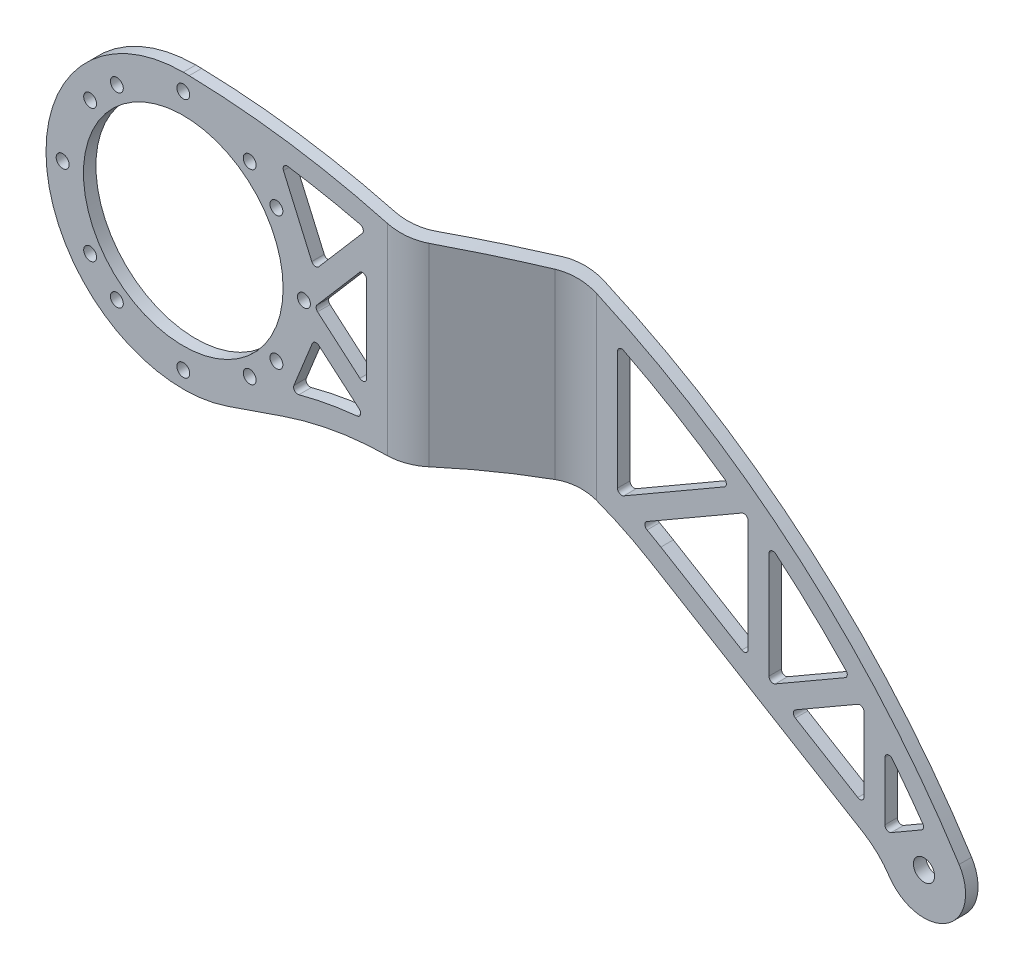
SolidWorks part; units mm, degrees
material "6061 合金"
ref_plane "前视基准面" through (0, 0, 0) normal (0, 0, 1) x (1, 0, 0)
ref_plane "上视基准面" through (0, 0, 0) normal (0, 1, 0) x (1, 0, 0)
ref_plane "右视基准面" through (0, 0, 0) normal (1, 0, 0) x (0, 0, -1)
other "Configuration Table"
sketch "草图1" plane through (0, 0, 0) normal (0, 0, 1) x (1, 0, 0)
  line L0 (-38.6665, 0) -> (31.2744, 0) construction
  line L1 (0, 22.4607) -> (0, -30.1372) construction
  line L4 (10.7304, -31.2067) -> (23.987, -26.6485)
  line L5 (91.2325, -33.7454) -> (142.3676, -64.5004)
  line L6 (157.0595, -65.0562) -> (0, 0) construction
  circle A7 centre (157.0595, -65.0562) radius 2.55
  arc A9 (0, 33) -> (10.7304, -31.2067) centre (0, 0) ccw
  arc A10 (148.7262, -70.5839) -> (165.4995, -59.6928) centre (157.0595, -65.0562) ccw
  arc A11 (1.4146, 32.9833) -> (165.4995, -59.6928) centre (-3.3007, -166.9611) cw
  arc A12 (23.987, -26.6485) -> (91.2325, -33.7454) centre (50, -102.3011) cw
  arc A13 (142.3676, -64.5004) -> (148.7262, -70.5839) centre (132.0595, -81.6393) cw
  arc A14 (1.4146, 32.9833) -> (0, 33) centre (0, -27) ccw
  dimension "D1" = 60
  dimension "D2" = 5.1
  dimension "D3" = 22.5
  dimension "D4" = 33
  dimension "D6" = 80
  dimension "D7" = 20
  dimension "D8" = 10
  dimension "D10" = 200
  dimension "D11" = 50
  dimension "D5" = 130
  dimension "D9" = 170
  dimension "D12" = 25
extrude "凸台-拉伸1" add sketch "草图1" along normal blind 3 and the other way blind 21
sketch "草图6" plane through (0, 0, 0) normal (0, 1, 0) x (1, 0, 0)
  line L0 (-33, 0) -> (47.8579, 0)
  line L2 (54.9289, 2.9289) -> (73, 21)
  line L3 (10.7304, 21) -> (-33, 21) construction
  line L5 (53.2426, -3) -> (71.3137, 15.0711)
  line L7 (78.3848, 18) -> (167.0595, 18)
  line L8 (167.0595, 18) -> (167.0595, -3)
  line L9 (167.0595, -3) -> (53.2426, -3)
  line L10 (73, 21) -> (-33, 21)
  line L12 (-33, 21) -> (-33, 0)
  line L13 (-33, 21) -> (-33, -3) construction
  line L14 (167.0595, -3) -> (167.0595, 21) construction
  line L15 (165.4995, 21) -> (1.4146, 21) construction
  line L16 (1.4146, -3) -> (165.4995, -3) construction
  arc A0 (71.3137, 15.0711) -> (78.3848, 18) centre (78.3848, 8) cw
  arc A1 (47.8579, 0) -> (54.9289, 2.9289) centre (47.8579, 10) ccw
  point P25 (52, 0)
  dimension "D5" = 10
  dimension "D1" = 3
  dimension "D2" = 3
  dimension "D3" = 45
  dimension "D4" = 85
extrude "切除-拉伸3" cut sketch "草图6" against normal through all both and the other way through all
sketch "草图2" plane through (0, 0, 3) normal (0, 0, 1) x (1, 0, 0)
  circle A0 centre (-29, 0) radius 1.55
  circle A2 centre (0, 0) radius 29 construction
  circle A3 centre (0, -29) radius 1.55
  circle A4 centre (0, 29) radius 1.55
  circle A5 centre (29, 0) radius 1.55
  dimension "D2" = 3.1
  dimension "D1" = 29
extrude "切除-拉伸1" cut sketch "草图2" against normal through all
sketch "草图4" plane through (0, 0, 3) normal (0, 0, 1) x (1, 0, 0)
  line L0 (35.2189, 0) -> (0, 0) construction
  line L1 (0, 0) -> (0, 39.685) construction
  line L2 (22.3882, 15.9693) -> (0, 0) construction
  line L3 (0, 0) -> (15.9693, 22.3882) construction
  line L4 (15.9693, -22.3882) -> (0, 0) construction
  line L5 (0, 0) -> (22.3882, -15.9693) construction
  line L6 (-22.3882, -15.9693) -> (0, 0) construction
  line L7 (0, 0) -> (-15.9693, -22.3882) construction
  line L8 (-15.9693, 22.3882) -> (0, 0) construction
  line L9 (0, 0) -> (-22.3882, 15.9693) construction
  circle A0 centre (0, 0) radius 27.5 construction
  circle A1 centre (-22.3882, 15.9693) radius 1.55
  circle A2 centre (15.9693, 22.3882) radius 1.55
  circle A3 centre (-15.9693, -22.3882) radius 1.55
  circle A4 centre (22.3882, -15.9693) radius 1.55
  circle A5 centre (-15.9693, 22.3882) radius 1.55
  circle A6 centre (22.3882, 15.9693) radius 1.55
  circle A7 centre (15.9693, -22.3882) radius 1.55
  circle A8 centre (-22.3882, -15.9693) radius 1.55
  point P16 (0, 0)
  dimension "D1" = 55
  dimension "D5" = 3.1
  dimension "D2" = 35.5
  dimension "D3" = 19
  dimension "D4" = 4
extrude "切除-拉伸2" cut sketch "草图4" against normal through all
fillet "圆角2" radius 10 2 edges at (73, -3.8831, -21) (53.2426, 1.2564, 3)
sketch "草图10" plane through (0, 0, 3) normal (0, 0, 1) x (1, 0, 0)
  circle A0 centre (0, 0) radius 24
  dimension "D1" = 48
extrude "切除-拉伸5" cut sketch "草图10" against normal through all
sketch "草图12" plane through (0, 0, -18) normal (0, 0, 1) x (1, 0, 0)
  line L0 (83.3848, 6.0917) -> (83.3848, -22.3996)
  line L1 (84.8848, -23.2657) -> (109.0475, -9.3153)
  line L4 (93.8095, -29.4607) -> (144.9447, -60.2157)
  line L5 (83.3848, 7.7118) -> (83.3848, -24.1317)
  line L11 (113.2813, -12.6445) -> (90.4641, -25.818)
  line L12 (93.8095, -29.4607) -> (113.2659, -41.1626)
  line L13 (114.7813, -13.5105) -> (114.7813, -40.3057)
  line L14 (119.7813, -17.8314) -> (119.7813, -43.3492)
  line L15 (121.2813, -44.2152) -> (138.1188, -34.4941)
  line L16 (126.1486, -47.1786) -> (141.1555, -38.5143)
  line L17 (142.6555, -39.3804) -> (142.6555, -57.0705)
  line L18 (147.6555, -46.3571) -> (147.6555, -60.3684)
  line L19 (126.1332, -48.9016) -> (141.1401, -57.9274)
  line L20 (156.4448, -57.026) -> (149.1555, -61.2345)
  arc A0 (109.124, -7.6322) -> (84.8368, 6.9837) centre (-3.3007, -166.9611) ccw
  arc A1 (138.3452, -32.9408) -> (121.4209, -17.0627) centre (-3.3007, -166.9611) ccw
  arc A2 (161.2795, -62.3745) -> (83.3848, 7.7118) centre (-3.3007, -166.9611) ccw
  arc A4 (156.7656, -55.5888) -> (149.4388, -45.7354) centre (-3.3007, -166.9611) ccw
  arc A5 (149.4263, -63.6561) -> (144.9447, -60.2157) centre (132.0595, -81.6393) ccw construction
  arc A22 (152.8929, -67.82) -> (144.9447, -60.2157) centre (132.0595, -81.6393) ccw
  arc A24 (152.8929, -67.82) -> (161.2795, -62.3745) centre (157.0595, -65.0562) ccw
  arc A25 (147.6555, -46.3571) -> (149.4388, -45.7354) centre (148.6555, -46.3571) cw
  arc A26 (126.1486, -47.1786) -> (126.1332, -48.9016) centre (126.6486, -48.0446) ccw
  arc A27 (141.1555, -38.5143) -> (142.6555, -39.3804) centre (141.6555, -39.3804) cw
  arc A28 (138.1188, -34.4941) -> (138.3452, -32.9408) centre (137.6188, -33.628) ccw
  arc A29 (119.7813, -43.3492) -> (121.2813, -44.2152) centre (120.7813, -43.3492) ccw
  arc A30 (119.7813, -17.8314) -> (121.4209, -17.0627) centre (120.7813, -17.8314) cw
  arc A31 (114.7813, -40.3057) -> (113.2659, -41.1626) centre (113.7813, -40.3057) cw
  arc A32 (90.4641, -25.818) -> (90.4877, -27.5633) centre (90.9641, -26.684) ccw
  arc A33 (113.2813, -12.6445) -> (114.7813, -13.5105) centre (113.7813, -13.5105) cw
  arc A34 (109.0475, -9.3153) -> (109.124, -7.6322) centre (108.5475, -8.4493) ccw
  arc A35 (84.8848, -23.2657) -> (83.3848, -22.3996) centre (84.3848, -22.3996) cw
  arc A36 (84.8368, 6.9837) -> (83.3848, 6.0917) centre (84.3848, 6.0917) ccw
  arc A37 (142.6555, -57.0705) -> (141.1401, -57.9274) centre (141.6555, -57.0705) cw
  arc A38 (147.6555, -60.3684) -> (149.1555, -61.2345) centre (148.6555, -60.3684) ccw
  arc A39 (156.7656, -55.5888) -> (156.4448, -57.026) centre (155.9448, -56.16) cw
  arc A41 (93.8095, -29.4607) -> (83.3848, -24.1317) centre (50, -102.3011) ccw
  arc A42 (93.8095, -29.4607) -> (90.4877, -27.5633) centre (50, -102.3011) ccw
  point P19 (83.3848, -24.1317)
  point P21 (147.6555, -62.1005)
  point P30 (147.6555, -62.1005)
  point P35 (124.6791, -48.027)
  point P38 (142.6555, -37.6483)
  point P41 (139.212, -33.8629)
  point P44 (399.0304, 162.0422)
  point P45 (119.7813, -45.0813)
  point P54 (114.7813, -11.7784)
  point P57 (110.3955, -8.537)
  dimension "D6" = 60
  dimension "D9" = 5
  dimension "D2" = 5
  dimension "D11" = 60
  dimension "D12" = 1
  dimension "D13" = 1
  dimension "D7" = 1
  dimension "D3" = 5
  dimension "D4" = 60
  dimension "D5" = 60
  dimension "D8" = 5
  dimension "D1" = 5
extrude "切除-拉伸6" cut sketch "草图12" against normal through all
sketch "草图13" plane through (0, 0, 3) normal (0, 0, 1) x (1, 0, 0)
  line L0 (32.9388, 0) -> (0, 0) construction
  line L2 (24.0827, 24.5625) -> (30.8907, 9.0204)
  line L3 (32.565, 8.7697) -> (43.0399, 20.9561)
  line L4 (44.1005, -17.5061) -> (44.1005, 22.19)
  line L5 (9.1045, -26.4784) -> (22.3612, -21.9202)
  line L6 (44.1005, -8.7346) -> (44.1005, 11.822)
  line L8 (32.1804, 0.6518) -> (42.3422, 12.4738)
  line L9 (32.2869, -0.7584) -> (42.4487, -9.493)
  line L10 (32.5853, -7.6081) -> (42.2904, -15.9502)
  line L11 (31.0063, -7.9916) -> (26.5896, -18.9173)
  circle A0 centre (22.3882, -15.9693) radius 1.55 construction
  arc A1 (41.7358, -17.7038) -> (42.2904, -15.9502) centre (41.6386, -16.7085) ccw
  arc A2 (26.5896, -18.9173) -> (27.7781, -20.2573) centre (27.5167, -19.2921) ccw
  arc A3 (32.1804, 0.6518) -> (32.2869, -0.7584) centre (32.9388, 0) ccw
  arc A4 (32.5853, -7.6081) -> (31.0063, -7.9916) centre (31.9335, -8.3664) ccw
  arc A5 (42.4487, -9.493) -> (44.1005, -8.7346) centre (43.1005, -8.7346) ccw
  arc A6 (42.3422, 12.4738) -> (44.1005, 11.822) centre (43.1005, 11.822) cw
  arc A7 (30.8907, 9.0204) -> (32.565, 8.7697) centre (31.8066, 9.4216) ccw
  arc A8 (43.0399, 20.9561) -> (42.5165, 22.5799) centre (42.2815, 21.6079) ccw
  arc A9 (24.0827, 24.5625) -> (25.1446, 25.9531) centre (24.9987, 24.9638) cw
  circle A10 centre (22.3882, 15.9693) radius 1.55 construction
  arc A18 (44.1005, -17.5061) -> (22.3612, -21.9202) centre (50, -102.3011) ccw
  arc A19 (44.1005, 22.19) -> (1.2967, 27.9847) centre (-3.3007, -166.9611) ccw
  arc A20 (1.2967, 27.9847) -> (0, 28) centre (0, -27) ccw
  arc A21 (0, 28) -> (9.1045, -26.4784) centre (0, 0) ccw
  arc A22 (41.7358, -17.7038) -> (27.7781, -20.2573) centre (50, -102.3011) ccw
  arc A23 (42.5165, 22.5799) -> (25.1446, 25.9531) centre (-3.3007, -166.9611) ccw
  point P24 (31.5286, -0.1065)
  point P27 (31.5286, -6.6998)
  point P30 (44.1005, -10.9128)
  point P33 (44.1005, 14.5195)
  point P36 (31.5286, 7.564)
  dimension "D6" = 5
  dimension "D7" = 1
  dimension "D2" = 5
  dimension "D3" = 5
  dimension "D4" = 5
  dimension "D1" = 5
extrude "切除-拉伸7" cut sketch "草图13" against normal through all
